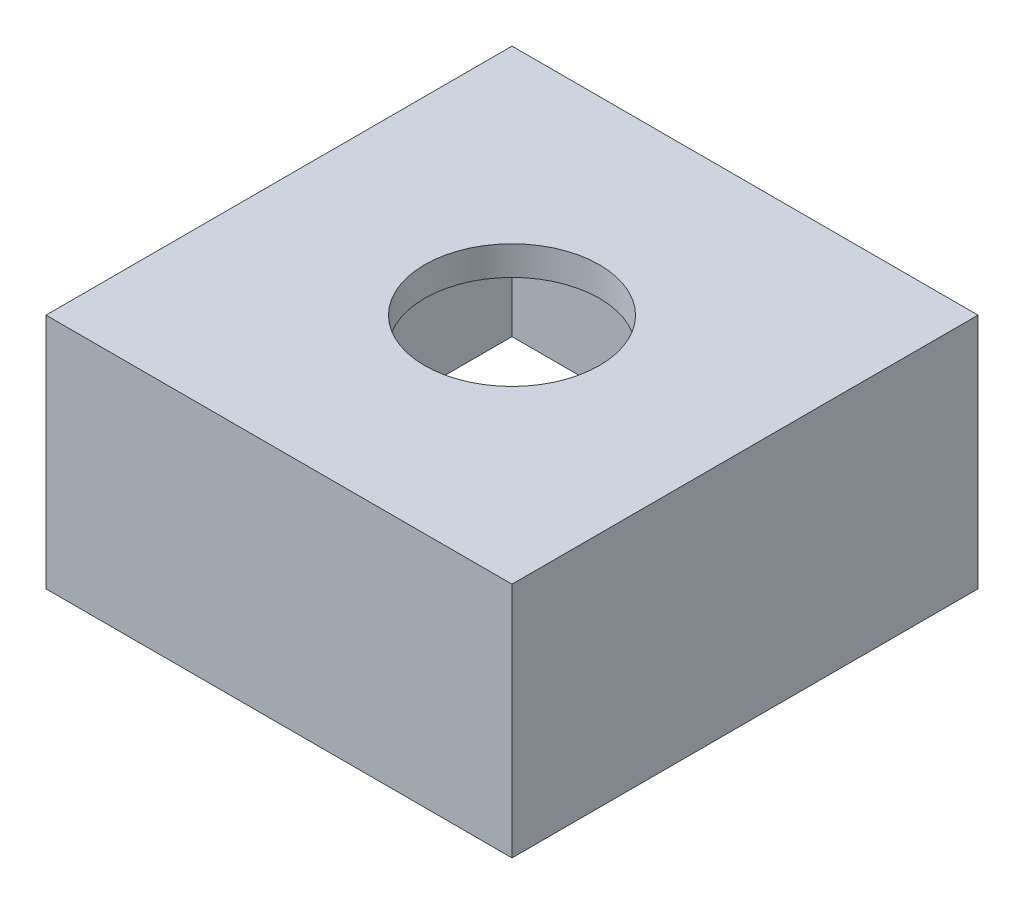
SolidWorks part; units mm, degrees
ref_plane "Front Plane" through (0, 0, 0) normal (0, 0, 1) x (1, 0, 0)
ref_plane "Top Plane" through (0, 0, 0) normal (0, 1, 0) x (1, 0, 0)
ref_plane "Right Plane" through (0, 0, 0) normal (1, 0, 0) x (0, 0, -1)
sketch "Sketch1" plane through (0, 0, 0) normal (0, 1, 0) x (1, 0, 0)
  line L1 (-101.6, -101.6) -> (101.6, -101.6)
  line L2 (-101.6, -101.6) -> (-101.6, 101.6)
  line L3 (-101.6, 101.6) -> (101.6, 101.6)
  line L4 (101.6, -101.6) -> (101.6, 101.6)
  line L5 (-101.6, -101.6) -> (101.6, 101.6) construction
  line L6 (-101.6, 101.6) -> (101.6, -101.6) construction
  line L7 (-95.25, -95.25) -> (95.25, -95.25)
  line L8 (-95.25, -95.25) -> (-95.25, 95.25)
  line L9 (-95.25, 95.25) -> (95.25, 95.25)
  line L10 (95.25, -95.25) -> (95.25, 95.25)
  line L11 (-95.25, -95.25) -> (95.25, 95.25) construction
  line L12 (-95.25, 95.25) -> (95.25, -95.25) construction
  point P0 (0, 0)
  point P6 (0, 0)
  dimension "D1" = 203.2
  dimension "D2" = 203.2
  dimension "D3" = 6.35
extrude "Boss-Extrude1" add sketch "Sketch1" along normal blind 90.678
sketch "Sketch2" plane through (0, 90.678, 0) normal (0, 1, 0) x (1, 0, 0)
  line L1 (-101.6, -101.6) -> (101.6, -101.6)
  line L2 (-101.6, -101.6) -> (-101.6, 101.6)
  line L3 (-101.6, 101.6) -> (101.6, 101.6)
  line L4 (101.6, -101.6) -> (101.6, 101.6)
  line L5 (-101.6, -101.6) -> (101.6, 101.6) construction
  line L6 (-101.6, 101.6) -> (101.6, -101.6) construction
  point P0 (0, 0)
extrude "Boss-Extrude2" add sketch "Sketch2" along normal blind 12.7
sketch "Sketch4" plane through (0, 103.378, 0) normal (0, 1, 0) x (1, 0, 0)
  circle A0 centre (0, 0) radius 38.1
  dimension "D1" = 76.2
extrude "Cut-Extrude3" cut sketch "Sketch4" against normal through all
